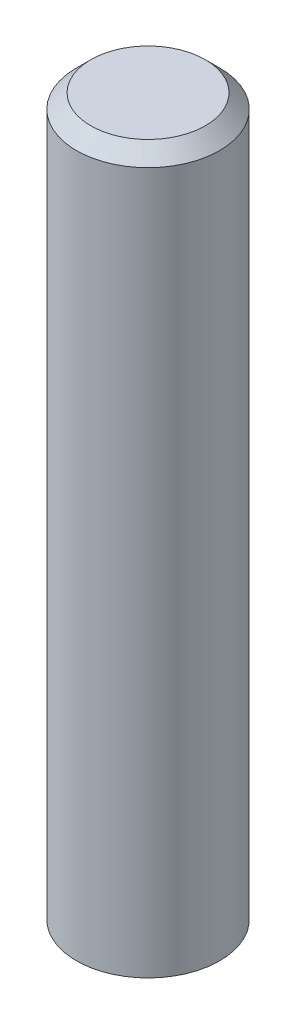
SolidWorks part; units mm, degrees
material "AISI 304"
ref_plane "Alzado" through (0, 0, 0) normal (0, 0, 1) x (1, 0, 0)
ref_plane "Planta" through (0, 0, 0) normal (0, 1, 0) x (1, 0, 0)
ref_plane "Vista lateral" through (0, 0, 0) normal (1, 0, 0) x (0, 0, -1)
sketch "Croquis1" plane through (0, 0, 0) normal (0, 0, 1) x (1, 0, 0)
  line L0 (0, 0) -> (0, 24.5) construction
  line L1 (0, 24.5) -> (0, 25)
  line L2 (0, 24.5) -> (-2, 24.5)
  line L3 (-2, 24.5) -> (-2, 0)
  line L4 (-2, 0) -> (-2.5, 0)
  line L5 (-2.5, 0) -> (-2.5, 24.5)
  line L6 (-2.5, 24.5) -> (-2, 25)
  line L7 (-2, 25) -> (0, 25)
  dimension "D1" = 25
  dimension "D2" = 0.5
  dimension "D3" = 2.5
  dimension "D4" = 0.5
  dimension "D5" = 45
  dimension "D6" = 0.5
revolve "Revolución1" add sketch "Croquis1" angle 360 about L0
